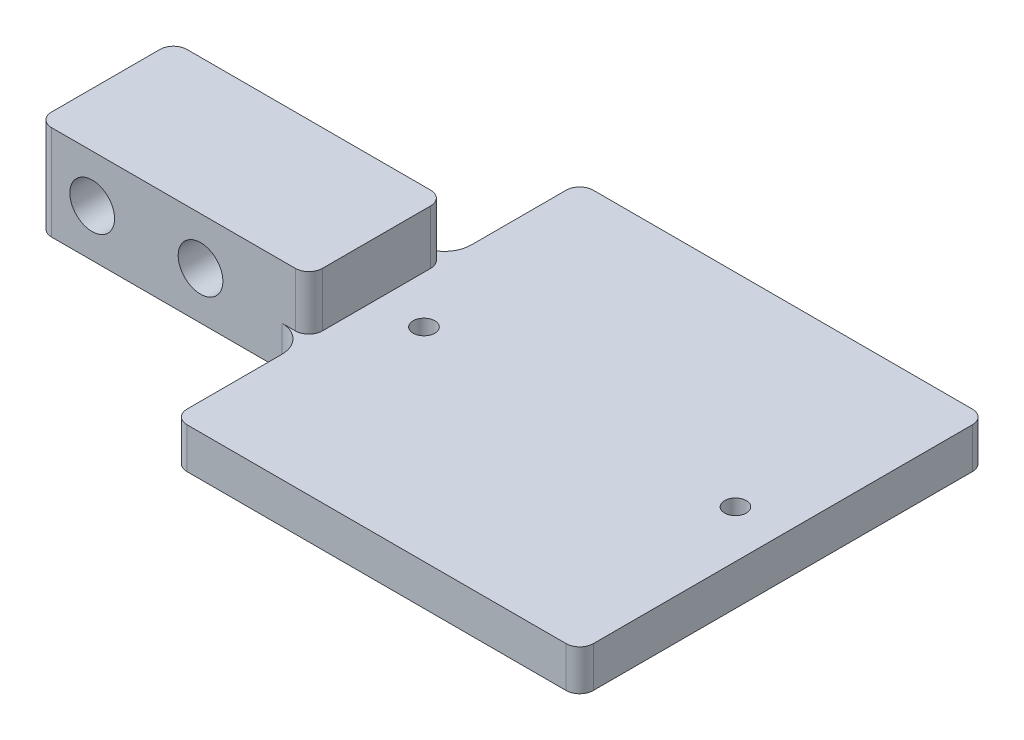
SolidWorks part; units mm, degrees
material "Brass"
ref_plane "Front Plane" through (0, 0, 0) normal (0, 0, 1) x (1, 0, 0)
ref_plane "Top Plane" through (0, 0, 0) normal (0, 1, 0) x (1, 0, 0)
ref_plane "Right Plane" through (0, 0, 0) normal (1, 0, 0) x (0, 0, -1)
sketch "Sketch1" plane through (0, 0, 0) normal (0, 1, 0) x (1, 0, 0)
  line L1 (0, 0) -> (30, 0)
  line L2 (0, 0) -> (0, 15)
  line L3 (0, 15) -> (30, 15)
  line L4 (30, 0) -> (30, 15)
  dimension "D1" = 15
  dimension "D2" = 30
extrude "Boss-Extrude1" add sketch "Sketch1" along normal blind 3
sketch "Sketch2" plane through (0, 0, 0) normal (-1, 0, 0) x (0, 0, 1)
  line L0 (-15, 0) -> (0, 0) construction
  line L1 (-10, 0) -> (-15, 0)
  line L2 (-10, 0) -> (-10, 7)
  line L3 (-10, 7) -> (-15, 7)
  line L4 (-15, 0) -> (-15, 7)
  dimension "D1" = 5
  dimension "D2" = 7
extrude "Boss-Extrude2" add sketch "Sketch2" along normal blind 20
sketch "Sketch3" plane through (-20, 0, 0) normal (-1, 0, 0) x (0, 0, 1)
  line L1 (-15, 2) -> (-15, 5)
  arc A0 (-15, 2) -> (-15, 5) centre (-15, 3.5) ccw
  dimension "D1" = 3
  dimension "D2" = 3.5
extrude "Cut-Extrude1" cut sketch "Sketch3" against normal blind 18
sketch "Sketch4" plane through (0, 3, 0) normal (0, 1, 0) x (1, 0, 0)
  line L0 (30, 15) -> (0, 15) construction
  line L1 (25.7, 15) -> (27.3, 15)
  line L2 (2.7, 15) -> (4.3, 15)
  line L3 (30, 0) -> (30, 15) construction
  line L4 (0, 15) -> (0, 10) construction
  arc A0 (25.7, 15) -> (27.3, 15) centre (26.5, 15) ccw
  arc A1 (2.7, 15) -> (4.3, 15) centre (3.5, 15) ccw
  dimension "D1" = 0.8
  dimension "D2" = 0.8
  dimension "D3" = 3.5
  dimension "D4" = 3.5
mirror "Mirror1" about plane through (0, 3, -15) normal (0, 0, 1) of bodies 103 104
sketch "Sketch5" plane through (0, 0, -10) normal (0, 0, 1) x (1, 0, 0)
  line L0 (-20, 0) -> (-20, 7) construction
  line L2 (-20, 7) -> (0, 7) construction
  circle A0 centre (-16, 3.5) radius 1.65
  circle A1 centre (-8, 3.5) radius 1.65
  dimension "D1" = 3.3
  dimension "D2" = 3.3
  dimension "D3" = 4
  dimension "D5" = 3.5
  dimension "D6" = 3.5
  dimension "D4" = 8
fillet "Fillet2" radius 2 2 edges at (0, 1.5, -10) (0, 1.5, -20)
fillet "Fillet3" radius 1 8 edges at (30, 1.5, 0) (0, 1.5, 0) (0, 1.5, -30) (30, 1.5, -30) (0, 5, -20) (-20, 3.5, -20) (0, 5, -10) (-20, 3.5, -10)
hole_wizard "M2x0.4 Tapped Hole1" positions "3DSketch1" profile "Sketch7" tap size "M2x0.4" standard "BSI" end condition through all
sketch3d "3DSketch1"
  point P0 (3.5, 3, -15)
  point P3 (26.5, 3, -15)
sketch "Sketch7" plane through (3.5, 3, -15) normal (1, 0, 0) x (0, 0, 1)
  line L0 (0, 0) -> (0, 3)
  line L1 (0, 3) -> (0.8, 3)
  line L2 (0.8, 3) -> (0.8, 0)
  line L5 (0.8, 0) -> (0, 0)
  line L11 (0, -6.35) -> (0, 107.95) construction
  dimension "Thru Tap Drill Dia." = 1.6
  dimension "Thru Tap Drill Depth" = 3
cosmetic thread "Hole Thread1" parameters "D2"=2
cosmetic thread "Hole Thread2" parameters "D2"=2
hole_wizard "M4x0.7 Tapped Hole1" positions "3DSketch2" profile "Sketch8" tap size "M4x0.7" standard "BSI" end condition through all
sketch3d "3DSketch2"
  point P0 (-16, 3.5, -10)
  point P3 (-8, 3.5, -10)
sketch "Sketch8" plane through (-16, 3.5, -10) normal (1, 0, 0) x (0, -1, 0)
  line L0 (0, 0) -> (0, 20)
  line L1 (0, 20) -> (1.65, 20)
  line L2 (1.65, 20) -> (1.65, 0)
  line L5 (1.65, 0) -> (0, 0)
  line L11 (0, -6.35) -> (0, 107.95) construction
  dimension "Thru Tap Drill Dia." = 3.3
  dimension "Thru Tap Drill Depth" = 20
cosmetic thread "Hole Thread3" parameters "D2"=4
cosmetic thread "Hole Thread4" parameters "D2"=4
equation "\"D2@Sketch4\"=\"D1@Sketch4\""
equation "\"D4@Sketch4\"=\"D3@Sketch4\""
equation "\"D2@Sketch5\"=\"D1@Sketch5\""
equation "\"D6@Sketch5\"=\"D5@Sketch5\""
